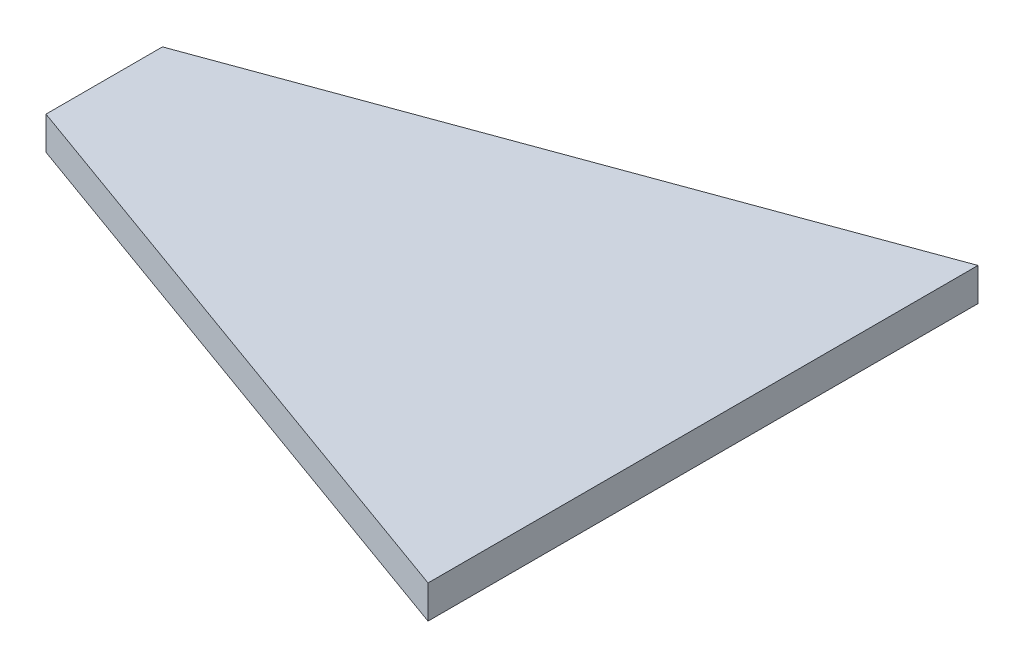
SolidWorks part; units mm, degrees
ref_plane "Plan de face" through (0, 0, 0) normal (0, 0, 1) x (1, 0, 0)
ref_plane "Plan de dessus" through (0, 0, 0) normal (0, 1, 0) x (1, 0, 0)
ref_plane "Plan de droite" through (0, 0, 0) normal (1, 0, 0) x (0, 0, -1)
sketch "Esquisse1" plane through (0, 0, 0) normal (0, 1, 0) x (1, 0, 0)
  line L0 (28.6859, 18.3157) -> (224.263, 89.8892)
  line L1 (28.6859, 18.3157) -> (28.6859, -18.3157)
  line L2 (28.6859, -18.3157) -> (224.263, -88.7477)
  line L3 (224.263, 89.8892) -> (224.263, -88.7477)
extrude "Extru.-Mince1" add sketch "Esquisse1" along normal blind 10 thin thin type one direction wall 1.5
sketch "Esquisse2" plane through (0, 10, 0) normal (0, 1, 0) x (1, 0, 0)
  line L4 (225.763, -90.8822) -> (225.763, 92.0354)
  line L5 (225.763, 92.0354) -> (27.1859, 19.3641)
  line L6 (27.1859, 19.3641) -> (27.1859, -19.3699)
  line L7 (27.1859, -19.3699) -> (225.763, -90.8822)
  line L8 (225.763, -90.8822) -> (225.763, 92.0354)
  line L9 (225.763, 92.0354) -> (27.1859, 19.3641)
  line L10 (27.1859, 19.3641) -> (27.1859, -19.3699)
  line L11 (27.1859, -19.3699) -> (225.763, -90.8822)
  dimension "D1" = 0
extrude "Boss.-Extru.1" add sketch "Esquisse2" along normal blind 1
